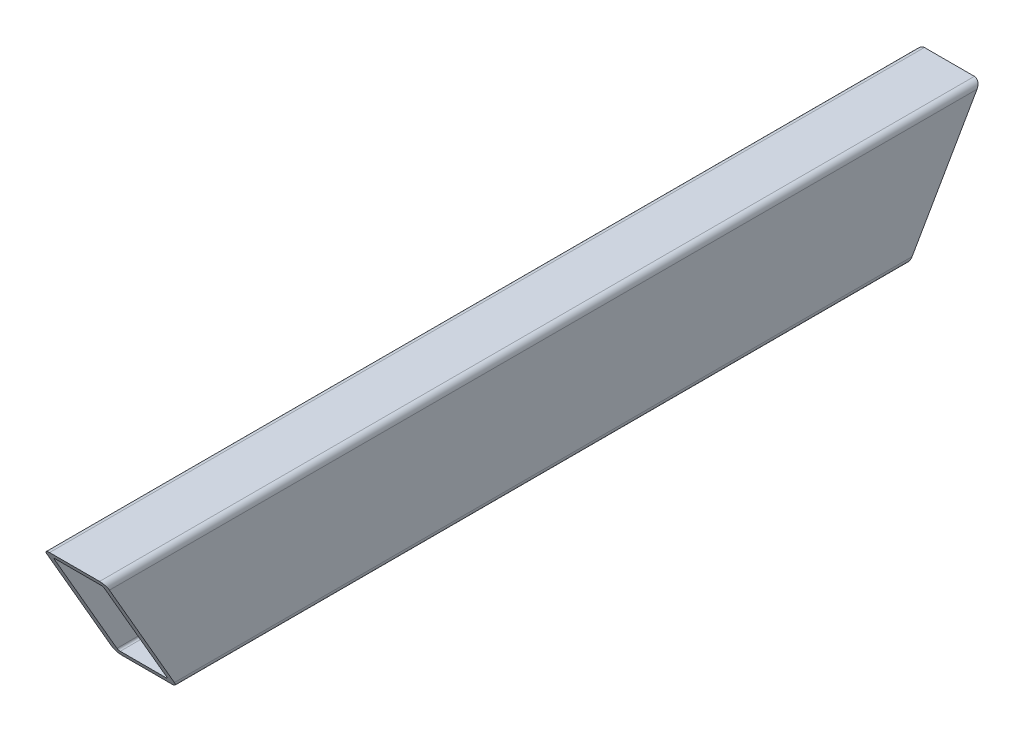
SolidWorks part; units mm, degrees
ref_plane "Płaszczyzna przednia" through (0, 0, 0) normal (0, 0, 1) x (1, 0, 0)
ref_plane "Płaszczyzna górna" through (0, 0, 0) normal (0, 1, 0) x (1, 0, 0)
ref_plane "Płaszczyzna prawa" through (0, 0, 0) normal (1, 0, 0) x (0, 0, -1)
sketch "Szkic1" plane through (0, 0, 0) normal (0, 0, 1) x (1, 0, 0)
  line L0 (-11, -3) -> (11, -3)
  line L1 (-12, -60) -> (12, -60)
  line L2 (-15, -57) -> (-15, -3)
  line L3 (-12, 0) -> (12, 0)
  line L4 (15, -57) -> (15, -3)
  line L5 (12, -56) -> (12, -4)
  line L6 (-11, -57) -> (11, -57)
  line L7 (-12, -56) -> (-12, -4)
  line L8 (-15, 0) -> (15, 0) construction
  line L9 (15, -60) -> (15, 0) construction
  line L10 (-15, -60) -> (15, -60) construction
  line L11 (-15, -60) -> (-15, 0) construction
  line L12 (-12, -3) -> (12, -3) construction
  line L13 (12, -57) -> (12, -3) construction
  line L14 (-12, -57) -> (12, -57) construction
  line L15 (-12, -57) -> (-12, -3) construction
  arc A0 (12, 0) -> (15, -3) centre (12, -3) cw
  arc A1 (15, -57) -> (12, -60) centre (12, -57) cw
  arc A2 (-12, -60) -> (-15, -57) centre (-12, -57) cw
  arc A3 (-15, -3) -> (-12, 0) centre (-12, -3) cw
  arc A4 (11, -3) -> (12, -4) centre (11, -4) cw
  arc A5 (12, -56) -> (11, -57) centre (11, -56) cw
  arc A6 (-11, -57) -> (-12, -56) centre (-11, -56) cw
  arc A7 (-12, -4) -> (-11, -3) centre (-11, -4) cw
  point P12 (15, 0)
  point P34 (0, 0)
  dimension "D4" = 3
  dimension "D1" = 1
  dimension "D2" = 30
  dimension "D5" = 60
  dimension "D3" = 3
extrude "Dodanie-wyciągnięcie1" add sketch "Szkic1" against normal blind 420
sketch "Szkic2" plane through (15, 0, 0) normal (1, 0, 0) x (0, 0, -1)
  line L1 (0, -60) -> (34.641, -60)
  line L2 (420, -60) -> (0, -60) construction
  line L5 (420, -60) -> (420, 0)
  line L6 (420, 0) -> (385.359, -60)
  line L7 (385.359, -60) -> (420, -60)
  line L15 (34.641, -60) -> (0, 0)
  line L19 (0, -60) -> (0, 0)
  dimension "D1" = 60
  dimension "D2" = 30
extrude "Wytnij-wyciągnięcie1" cut sketch "Szkic2" against normal up to surface (30 mm away) up to face at (-15, -30, -210)
sketch "Szkic4" [suppressed] plane through (15, 0, 0) normal (1, 0, 0) x (0, 0, -1)
  line L0 (0, -60) -> (34.641, 0)
  line L1 (1700, 0) -> (0, 0) construction
  line L2 (34.641, 0) -> (0, 0)
  line L3 (0, 0) -> (0, -60)
  line L5 (1614.282, 0) -> (1614.282, -60)
  line L6 (1700, -60) -> (0, -60) construction
  line L7 (1614.282, -60) -> (1579.641, 0)
  line L8 (1579.641, 0) -> (1614.282, 0)
  line L9 (1614.282, 0) -> (1700, 0)
  line L10 (1614.282, 0) -> (1614.282, -60)
  line L11 (1614.282, -60) -> (1700, -60)
  line L12 (1700, 0) -> (1700, -60)
  line M6 (0, -3) -> (0, -57)
  line M7 (0, -57) -> (1700, -57)
  line M8 (1700, -57) -> (1700, -3)
  line M9 (1700, -3) -> (0, -3)
  dimension "D1" = 30
  dimension "D2" = 30
  dimension "D3" = 1545
extrude "Wytnij-wyciągnięcie3" [suppressed] cut sketch "Szkic4" against normal blind 373 contours L5 M9 M7 M8 | L7 L5 M7 M9 | L8 L7 L5 M9 | L12 L9 L5 M9 | L12 L5 L11 M7 | L7 L5 M7 | L0 M7 M9 M6 | L2 L3 L0 M9 | L3 L0 M7
